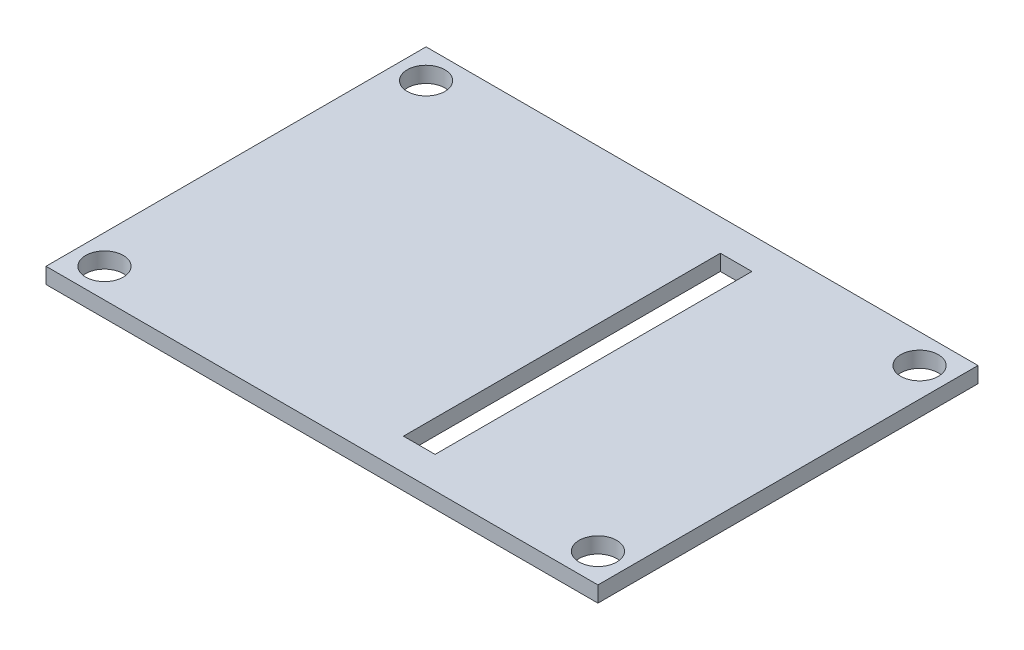
SolidWorks part; units mm, degrees
ref_plane "Front Plane" through (0, 0, 0) normal (0, 0, 1) x (1, 0, 0)
ref_plane "Top Plane" through (0, 0, 0) normal (0, 1, 0) x (1, 0, 0)
ref_plane "Right Plane" through (0, 0, 0) normal (1, 0, 0) x (0, 0, -1)
sketch "Sketch1" plane through (0, 0, 0) normal (0, 1, 0) x (1, 0, 0)
  line L1 (-34.1834, 14.9942) -> (35.6666, 14.9942)
  line L2 (-34.1834, 14.9942) -> (-34.1834, -33.1058)
  line L3 (-34.1834, -33.1058) -> (35.6666, -33.1058)
  line L4 (35.6666, 14.9942) -> (35.6666, -33.1058)
  line L5 (7.0566, 10.9942) -> (11.0566, 10.9942)
  line L6 (7.0566, 10.9942) -> (7.0566, -29.1058)
  line L7 (7.0566, -29.1058) -> (11.0566, -29.1058)
  line L8 (11.0566, 10.9942) -> (11.0566, -29.1058)
  point P8 (9.0566, 10.9942)
  dimension "D1" = 69.85
  dimension "D2" = 48.1
  dimension "D3" = 4
  dimension "D4" = 40.1
  dimension "D5" = 4
  dimension "D6" = 41.24
extrude "Boss-Extrude1" add sketch "Sketch1" along normal blind 2
sketch "Sketch2" plane through (0, 2, 0) normal (0, 1, 0) x (1, 0, 0)
  line L0 (-34.1834, 14.9942) -> (-34.1834, -33.1058) construction
  line L1 (-34.1834, -33.1058) -> (35.6666, -33.1058) construction
  circle A0 centre (-30.4834, -29.4058) radius 2.3813
  dimension "D1" = 3.7
  dimension "D2" = 3.7
extrude "Cut-Extrude1" cut sketch "Sketch2" against normal blind 2
sketch "Sketch3" plane through (0, 2, 0) normal (0, 1, 0) x (1, 0, 0)
  line L0 (35.6666, 14.9942) -> (-34.1834, 14.9942) construction
  line L1 (-34.1834, 14.9942) -> (-34.1834, -33.1058) construction
  circle A0 centre (-30.4834, 11.2942) radius 2.3813
  dimension "D1" = 3.7
  dimension "D2" = 3.7
extrude "Cut-Extrude2" cut sketch "Sketch3" against normal blind 2
sketch "Sketch4" plane through (0, 2, 0) normal (0, 1, 0) x (1, 0, 0)
  line L0 (-34.1834, -33.1058) -> (35.6666, -33.1058) construction
  line L1 (35.6666, -33.1058) -> (35.6666, 14.9942) construction
  circle A0 centre (31.9666, -29.4058) radius 2.3812
  dimension "D1" = 3.7
  dimension "D2" = 3.7
extrude "Cut-Extrude3" cut sketch "Sketch4" against normal blind 2
sketch "Sketch5" plane through (0, 2, 0) normal (0, 1, 0) x (1, 0, 0)
  line L0 (35.6666, 14.9942) -> (-34.1834, 14.9942) construction
  line L1 (35.6666, -33.1058) -> (35.6666, 14.9942) construction
  circle A0 centre (31.9666, 11.2942) radius 2.3812
  dimension "D1" = 3.7
  dimension "D2" = 3.7
extrude "Cut-Extrude4" cut sketch "Sketch5" against normal blind 2
